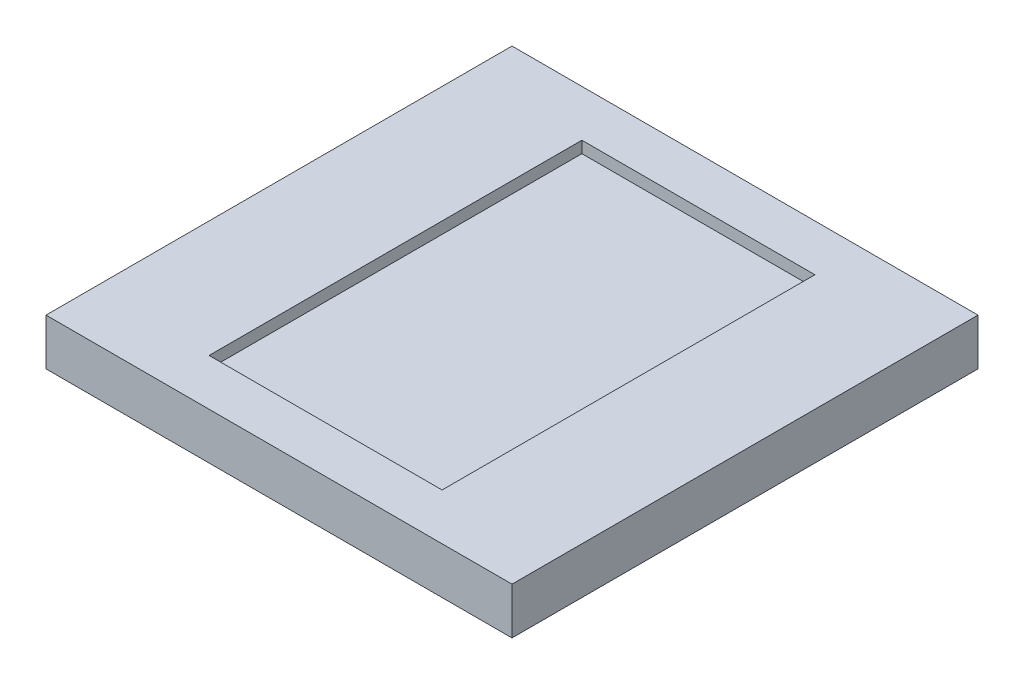
SolidWorks part; units mm, degrees
ref_plane "Plan de face" through (0, 0, 0) normal (0, 0, 1) x (1, 0, 0)
ref_plane "Plan de dessus" through (0, 0, 0) normal (0, 1, 0) x (1, 0, 0)
ref_plane "Plan de droite" through (0, 0, 0) normal (1, 0, 0) x (0, 0, -1)
sketch "Esquisse1" plane through (0, 0, 0) normal (0, 1, 0) x (1, 0, 0)
  line L1 (0, 0) -> (10, 0)
  line L2 (0, 0) -> (0, 10)
  line L3 (0, 10) -> (10, 10)
  line L4 (10, 0) -> (10, 10)
  dimension "D1" = 10
  dimension "D2" = 10
extrude "Boss.-Extru.1" add sketch "Esquisse1" along normal blind 1
sketch "Esquisse3" plane through (0, 1, 0) normal (0, 1, 0) x (1, 0, 0)
  line L0 (0, 10) -> (0, 0) construction
  line L1 (2.5, 9) -> (7.5, 9)
  line L2 (2.5, 9) -> (2.5, 1)
  line L3 (2.5, 1) -> (7.5, 1)
  line L4 (7.5, 9) -> (7.5, 1)
  line L5 (10, 0) -> (10, 10) construction
  line L6 (10, 10) -> (0, 10) construction
  line L7 (0, 0) -> (10, 0) construction
  dimension "D1" = 2.5
  dimension "D2" = 2.5
  dimension "D3" = 1
  dimension "D4" = 1
extrude "Enlèv. mat.-Extru.1" cut sketch "Esquisse3" against normal blind 0.25
